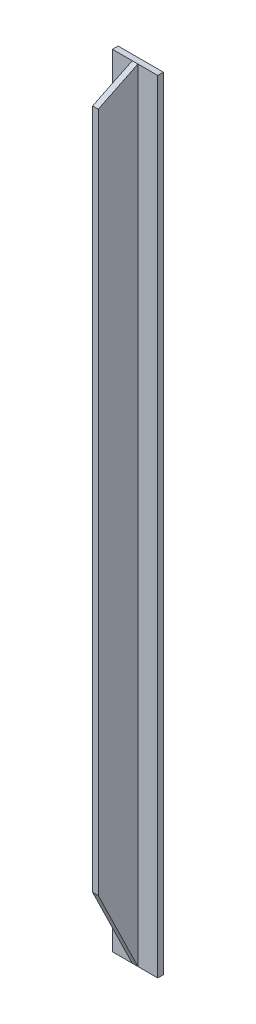
SolidWorks part; units mm, degrees
ref_plane "Front Plane" through (0, 0, 0) normal (0, 0, 1) x (1, 0, 0)
ref_plane "Top Plane" through (0, 0, 0) normal (0, 1, 0) x (1, 0, 0)
ref_plane "Right Plane" through (0, 0, 0) normal (1, 0, 0) x (0, 0, -1)
sketch "Sketch2" plane through (0, 0, 0) normal (0, 1, 0) x (1, 0, 0)
  line L1 (0, 0) -> (3.175, 0)
  line L2 (0, 0) -> (0, 22.225)
  line L4 (3.175, 0) -> (3.175, 22.225)
  line L7 (14.2875, 22.225) -> (3.175, 22.225)
  line L8 (14.2875, 22.225) -> (14.2875, 25.4)
  line L9 (14.2875, 25.4) -> (-11.1125, 25.4)
  line L10 (-11.1125, 22.225) -> (-11.1125, 25.4)
  line L14 (0, 22.225) -> (-11.1125, 22.225)
  point P0 (0, 0)
  point P3 (0, 0)
  dimension "D1" = 25.4
  dimension "D2" = 25.4
  dimension "D3" = 3.175
  dimension "D4" = 3.175
extrude "Boss-Extrude1" add sketch "Sketch2" along normal blind 438.15
sketch "Sketch4" plane through (3.175, 0, 0) normal (1, 0, 0) x (0, 0, -1)
  line L5 (22.225, 0) -> (0, 45.568)
  line L6 (0, 438.15) -> (0, 0) construction
  line L7 (0, 45.568) -> (0, 0)
  line L8 (0, 0) -> (22.225, 0)
  line L9 (22.225, 438.15) -> (0, 427.3101)
  line L10 (0, 427.3101) -> (0, 438.15)
  line L11 (0, 438.15) -> (22.225, 438.15)
  dimension "D1" = 26
  dimension "D2" = 64
extrude "Cut-Extrude1" cut sketch "Sketch4" against normal blind 438.15
